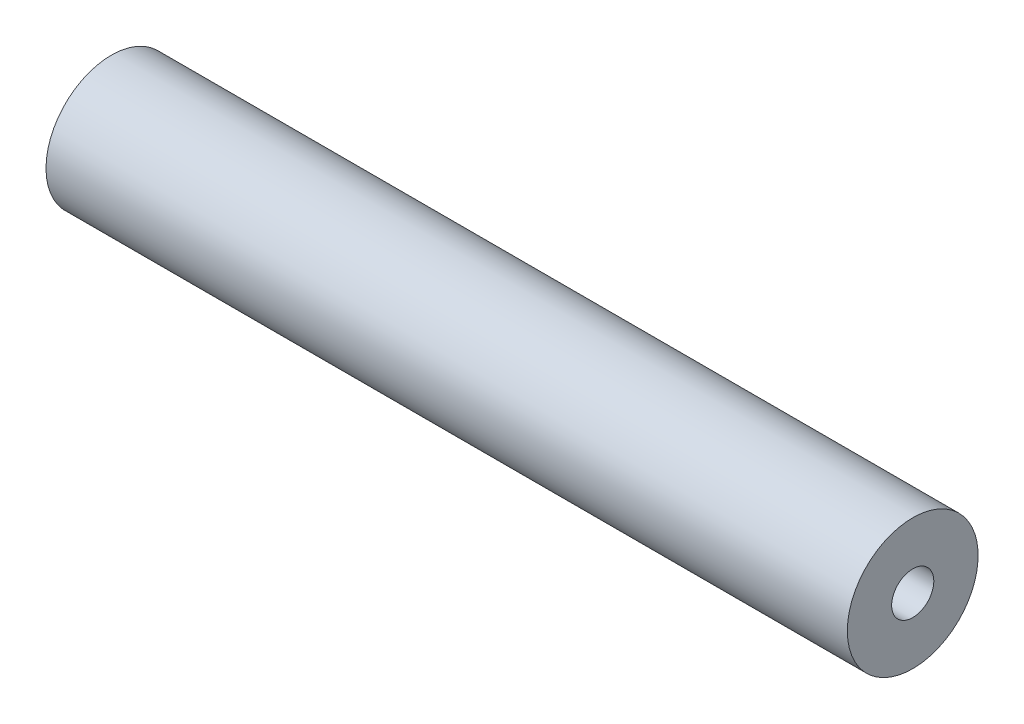
SolidWorks part; units mm, degrees
ref_plane "Ön Düzlem" through (0, 0, 0) normal (0, 0, 1) x (1, 0, 0)
ref_plane "Üst Düzlem" through (0, 0, 0) normal (0, 1, 0) x (1, 0, 0)
ref_plane "Sağ Düzlem" through (0, 0, 0) normal (1, 0, 0) x (0, 0, -1)
ref_plane "Düzlem1" through (0, 0, 0) normal (0, 0, -1) x (-1, 0, 0)
sketch "Çizim1" plane through (0, 0, 0) normal (0, 0, -1) x (-1, 0, 0)
  line L0 (-153, 12.4054) -> (-153, 0)
  line L1 (-153, 0) -> (-1, 0)
  line L2 (-1, 0) -> (-1, 12.4054)
  line L3 (-1, 12.4054) -> (-153, 12.4054)
  line L4 (-153, 0) -> (-1, 0) construction
  dimension "D1" = 152
revolve "Döndür1" add sketch "Çizim1" angle 360 about L4
sketch "Çizim2" plane through (153, 0, 0) normal (1, 0, 0) x (0, 0, -1)
  circle A3 centre (0, 0) radius 4
extrude "Kes-Ekstrüzyon1" cut sketch "Çizim2" against normal blind 21
sketch "Çizim3" plane through (1, 0, 0) normal (-1, 0, 0) x (0, 0, 1)
  arc A0 (1.5, -3.7081) -> (-1.5, -3.7081) centre (0, 0) ccw
  arc A1 (-1.5, -3.7081) -> (1.5, -3.7081) centre (0, 0) ccw
  dimension "D1" = 4
extrude "Kes-Ekstrüzyon2" cut sketch "Çizim3" against normal blind 21
